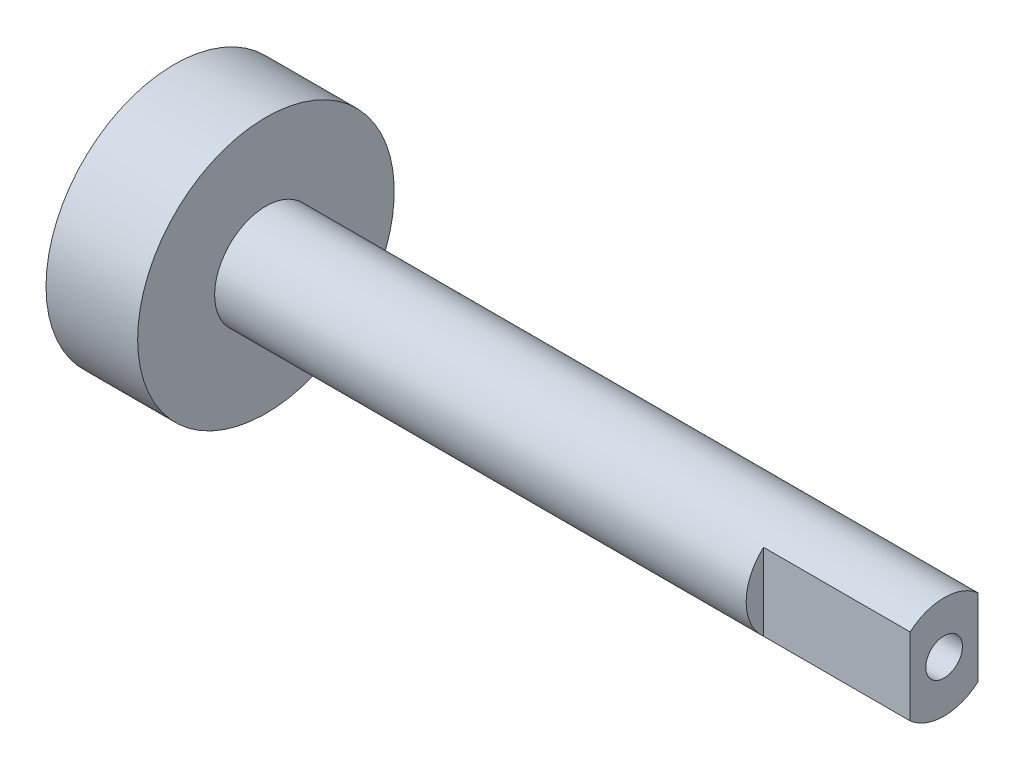
SolidWorks part; units mm, degrees
ref_plane "Front Plane" through (0, 0, 0) normal (0, 0, 1) x (1, 0, 0)
ref_plane "Top Plane" through (0, 0, 0) normal (0, 1, 0) x (1, 0, 0)
ref_plane "Right Plane" through (0, 0, 0) normal (1, 0, 0) x (0, 0, -1)
sketch "Sketch1" plane through (0, 0, 0) normal (1, 0, 0) x (0, 0, -1)
  circle A0 centre (0, 0) radius 2.8
  dimension "D1" = 5.6
extrude "Boss-Extrude1" add sketch "Sketch1" along normal mid plane 37
sketch "Sketch2" plane through (18.5, 0, 0) normal (1, 0, 0) x (0, 0, -1)
  line L0 (-1.85, 2.1018) -> (-1.85, -2.1018)
  line L1 (1.85, 2.1018) -> (1.85, -2.1018)
  arc A0 (-1.85, 2.1018) -> (-1.85, -2.1018) centre (0, 0) ccw
  arc A1 (1.85, -2.1018) -> (1.85, 2.1018) centre (0, 0) ccw
  dimension "D3" = 5.6
  dimension "D1" = 3.7
  dimension "D2" = 1.85
extrude "Cut-Extrude1" cut sketch "Sketch2" against normal blind 8
sketch "Sketch3" plane through (18.5, 0, 0) normal (1, 0, 0) x (0, 0, -1)
  circle A0 centre (0, 0) radius 1
  dimension "D1" = 2
extrude "Cut-Extrude2" cut sketch "Sketch3" against normal blind 6
ref_plane "Plane1" through (-18.5, 0, 0) normal (-1, 0, 0) x (0, 0, 1)
sketch "Sketch5" plane through (-18.5, 0, 0) normal (-1, 0, 0) x (0, 0, 1)
  circle A0 centre (0, 0) radius 7
  dimension "D1" = 14
extrude "Boss-Extrude2" add sketch "Sketch5" along normal blind 5 contours A0
ref_plane "Plane2" through (10.5, 0, 0) normal (1, 0, 0) x (0, 0, -1)
equation "\"shaftdiameter\"= 5.6"
equation "\"D1@Sketch1\"=\"shaftdiameter\""
equation "\"D3@Sketch2\"=\"shaftdiameter\""
equation "\"motor_cut\"= 8"
equation "\"D1@Cut-Extrude1\"=\"motor_cut\""
